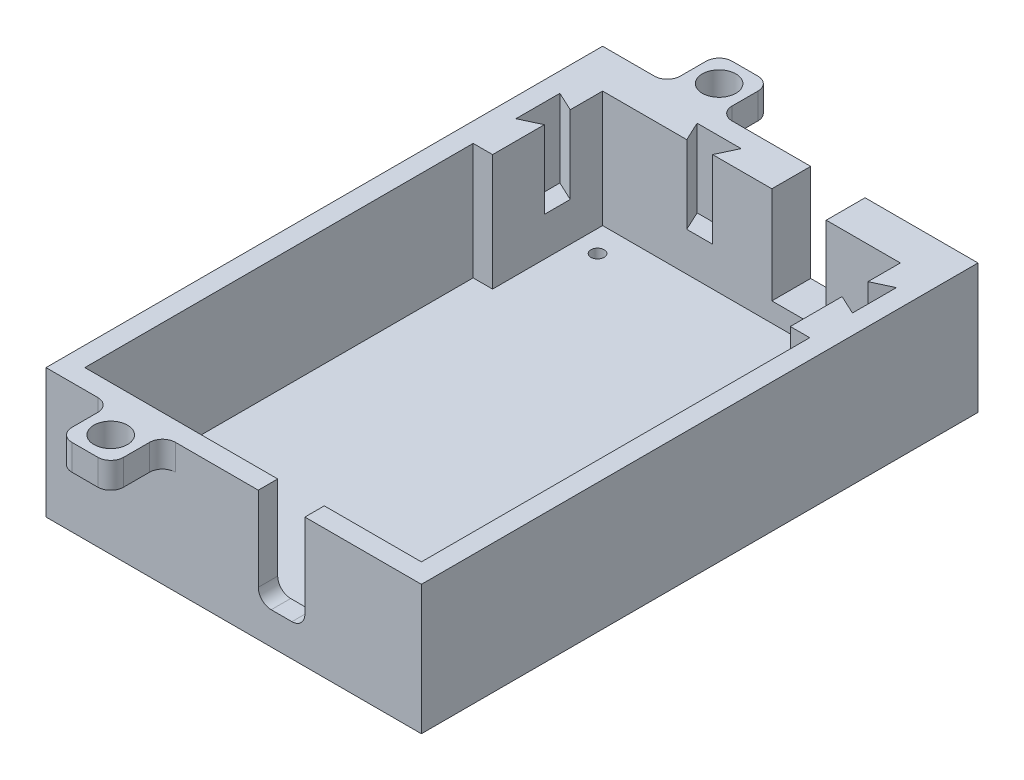
SolidWorks part; units mm, degrees
ref_plane "Front Plane" through (0, 0, 0) normal (0, 0, 1) x (1, 0, 0)
ref_plane "Top Plane" through (0, 0, 0) normal (0, 1, 0) x (1, 0, 0)
ref_plane "Right Plane" through (0, 0, 0) normal (1, 0, 0) x (0, 0, -1)
sketch "Sketch1" plane through (0, 0, 0) normal (0, 1, 0) x (1, 0, 0)
  line L1 (0, 0) -> (66.04, 0)
  line L2 (0, 0) -> (0, 101.6)
  line L3 (0, 101.6) -> (66.04, 101.6)
  line L4 (66.04, 0) -> (66.04, 101.6)
  dimension "D1" = 101.6
  dimension "D2" = 66.04
extrude "Base Extrude" add sketch "Sketch1" along normal blind 2.54
sketch "Sketch2" plane through (0, 0, 0) normal (0, -1, 0) x (1, 0, 0)
  line L1 (0, 0) -> (66.04, 0)
  line L2 (0, 0) -> (0, -101.6)
  line L3 (0, -101.6) -> (66.04, -101.6)
  line L4 (66.04, 0) -> (66.04, -101.6)
  line L5 (-3.81, 3.81) -> (69.85, 3.81)
  line L6 (-3.81, 3.81) -> (-3.81, -105.41)
  line L7 (-3.81, -105.41) -> (69.85, -105.41)
  line L8 (69.85, 3.81) -> (69.85, -105.41)
  dimension "D1" = 3.81
  dimension "D2" = 3.81
  dimension "D3" = 3.81
  dimension "D4" = 3.81
extrude "Walls" add sketch "Sketch2" against normal blind 25.4
sketch "Sketch3" plane through (0, 25.4, 0) normal (0, 1, 0) x (1, 0, 0)
  line L0 (66.04, 101.6) -> (66.04, 0) construction
  line L1 (0, 101.6) -> (66.04, 101.6)
  line L2 (0, 101.6) -> (0, 76.2)
  line L3 (0, 76.2) -> (3.81, 76.2)
  line L4 (66.04, 101.6) -> (66.04, 76.2)
  line L5 (0, 93.2166) -> (3.81, 91.44)
  line L6 (3.81, 76.2) -> (3.81, 86.36)
  line L7 (3.81, 86.36) -> (0, 84.5834)
  line L8 (0, 101.6) -> (0, 0) construction
  line L9 (3.81, 91.44) -> (3.81, 97.79)
  line L10 (3.81, 97.79) -> (20.32, 97.79)
  line L11 (20.32, 97.79) -> (18.5434, 101.6)
  line L12 (18.5434, 101.6) -> (27.1766, 101.6)
  line L13 (27.1766, 101.6) -> (25.4, 97.79)
  line L14 (25.4, 97.79) -> (62.23, 97.79)
  line L15 (62.23, 97.79) -> (62.23, 91.44)
  line L16 (62.23, 91.44) -> (66.04, 93.2166)
  line L17 (66.04, 93.2166) -> (66.04, 84.5834)
  line L18 (66.04, 84.5834) -> (62.23, 86.36)
  line L19 (62.23, 86.36) -> (62.23, 76.2)
  line L20 (62.23, 76.2) -> (66.04, 76.2)
  line L21 (66.04, 0) -> (66.04, 101.6) construction
  line L22 (3.81, 91.44) -> (3.81, 86.36) construction
  line L23 (20.32, 97.79) -> (25.4, 97.79) construction
  point P11 (3.81, 88.9)
  point P26 (22.86, 97.79)
  line M17 (0, 0) -> (0, 101.6)
  line M18 (0, 101.6) -> (66.04, 101.6)
  line M19 (66.04, 101.6) -> (66.04, 0)
  dimension "D1" = 115
  dimension "D2" = 3.81
  dimension "D3" = 25.4
  dimension "D4" = 12.7
  dimension "D5" = 5.08
  dimension "D6" = 5.08
  dimension "D7" = 3.81
  dimension "D8" = 19.05
extrude "Button Guide" add sketch "Sketch3" against normal up to surface (22.86 mm away) contours L6 L7 L3 M17 | L10 L11 L2 L5 L9 M18 | L15 L16 L13 L14 M19 M18 | L19 L20 L18 M19 up to face at (33.02, 2.54, -50.8)
sketch "Sketch4" plane through (0, 2.54, 0) normal (0, 1, 0) x (1, 0, 0)
  circle A0 centre (8.0645, 92.5426) radius 1.3
  circle A1 centre (57.9755, 92.5426) radius 1.3
  circle A2 centre (8.0645, 7.4526) radius 1.3
  circle A3 centre (57.9755, 7.4526) radius 1.3
  dimension "D1" = 2.6
extrude "Cut-Extrude1" cut sketch "Sketch4" against normal through all
sketch "Sketch5" plane through (0, 2.54, 0) normal (0, 1, 0) x (1, 0, 0)
  line L0 (0, 93.2166) -> (0, 84.5834)
  line L1 (0, 84.5834) -> (3.81, 86.36)
  line L2 (3.81, 86.36) -> (3.81, 91.44)
  line L3 (3.81, 91.44) -> (0, 93.2166)
  line L4 (18.5434, 101.6) -> (27.1766, 101.6)
  line L5 (27.1766, 101.6) -> (25.4, 97.79)
  line L6 (25.4, 97.79) -> (20.32, 97.79)
  line L7 (20.32, 97.79) -> (18.5434, 101.6)
  line L8 (62.23, 91.44) -> (66.04, 93.2166)
  line L9 (66.04, 93.2166) -> (66.04, 84.5834)
  line L10 (66.04, 84.5834) -> (62.23, 86.36)
  line L11 (62.23, 86.36) -> (62.23, 91.44)
extrude "Hard stop" add sketch "Sketch5" along normal blind 7.62
sketch "Sketch6" plane through (0, 25.4, 0) normal (0, 1, 0) x (1, 0, 0)
  line L0 (66.04, 0) -> (0, 0) construction
  line L1 (37.846, 0) -> (46.99, 0)
  line L2 (37.846, 0) -> (37.846, -3.81)
  line L3 (37.846, -3.81) -> (46.99, -3.81)
  line L4 (46.99, 0) -> (46.99, -3.81)
  line L5 (69.85, -3.81) -> (-3.81, -3.81) construction
  line L6 (69.85, 105.41) -> (69.85, -3.81) construction
  line L7 (-3.81, 105.41) -> (69.85, 105.41) construction
  line L8 (37.0205, 105.41) -> (47.6885, 105.41)
  line L9 (37.0205, 105.41) -> (37.0205, 97.79)
  line L10 (37.0205, 97.79) -> (47.6885, 97.79)
  line L11 (47.6885, 105.41) -> (47.6885, 97.79)
  line L12 (25.4, 97.79) -> (62.23, 97.79) construction
  line L13 (38.5445, 93.8126) -> (46.1645, 93.8126) construction
  point P18 (42.3545, 93.8126)
  point P19 (42.3545, 105.41)
  dimension "D1" = 22.86
  dimension "D2" = 9.144
  dimension "D4" = 10.668
extrude "Electronics Holes" cut sketch "Sketch6" against normal blind 19.05 contours L11 L10 L9 L8 | L1 L4 L3 L2
fillet "Fillet1" radius 2.54 2 edges at (46.99, 6.35, 1.905) (37.846, 6.35, 1.905)
sketch "Sketch7" plane through (0, 0, 3.81) normal (0, 0, 1) x (1, 0, 0)
  line L0 (37.846, 25.4) -> (-3.81, 25.4) construction
  line L1 (8.89, 25.4) -> (19.05, 25.4)
  line L2 (8.89, 25.4) -> (8.89, 20.32)
  line L3 (8.89, 20.32) -> (19.05, 20.32)
  line L4 (19.05, 25.4) -> (19.05, 20.32)
  line L6 (-3.81, 25.4) -> (-3.81, 0) construction
  point P10 (0, 0)
  dimension "D1" = 12.7
  dimension "D2" = 5.08
  dimension "D3" = 10.16
extrude "Boss-Extrude1" add sketch "Sketch7" along normal blind 10.16
sketch "Sketch8" plane through (0, 0, -105.41) normal (0, 0, -1) x (-1, 0, 0)
  line L1 (-19.05, 25.4) -> (-8.89, 25.4)
  line L2 (-19.05, 25.4) -> (-19.05, 20.32)
  line L3 (-19.05, 20.32) -> (-8.89, 20.32)
  line L4 (-8.89, 25.4) -> (-8.89, 20.32)
extrude "Boss-Extrude2" add sketch "Sketch8" along normal blind 10.16
sketch "Sketch9" plane through (0, 25.4, 0) normal (0, 1, 0) x (1, 0, 0)
  line L0 (8.89, 115.57) -> (19.05, 115.57) construction
  line L1 (8.89, 115.57) -> (8.89, 105.41) construction
  line L2 (8.89, -13.97) -> (8.89, -3.81) construction
  line L3 (19.05, -13.97) -> (8.89, -13.97) construction
  circle A0 centre (13.97, 110.49) radius 3.302
  circle A1 centre (13.97, -8.89) radius 3.302
  point P4 (13.97, 115.57)
  point P5 (8.89, 110.49)
  point P8 (13.97, -13.97)
  point P11 (0, 0)
  point P12 (8.89, -8.89)
  point P17 (0, 0)
  dimension "D1" = 6.604
extrude "Cut-Extrude2" cut sketch "Sketch9" against normal through all
fillet "Fillet2" radius 2.54 8 edges at (19.05, 22.86, 3.81) (19.05, 22.86, 13.97) (8.89, 22.86, 13.97) (8.89, 22.86, 3.81) (19.05, 22.86, -115.57) (19.05, 22.86, -105.41) (8.89, 22.86, -105.41) (8.89, 22.86, -115.57)
